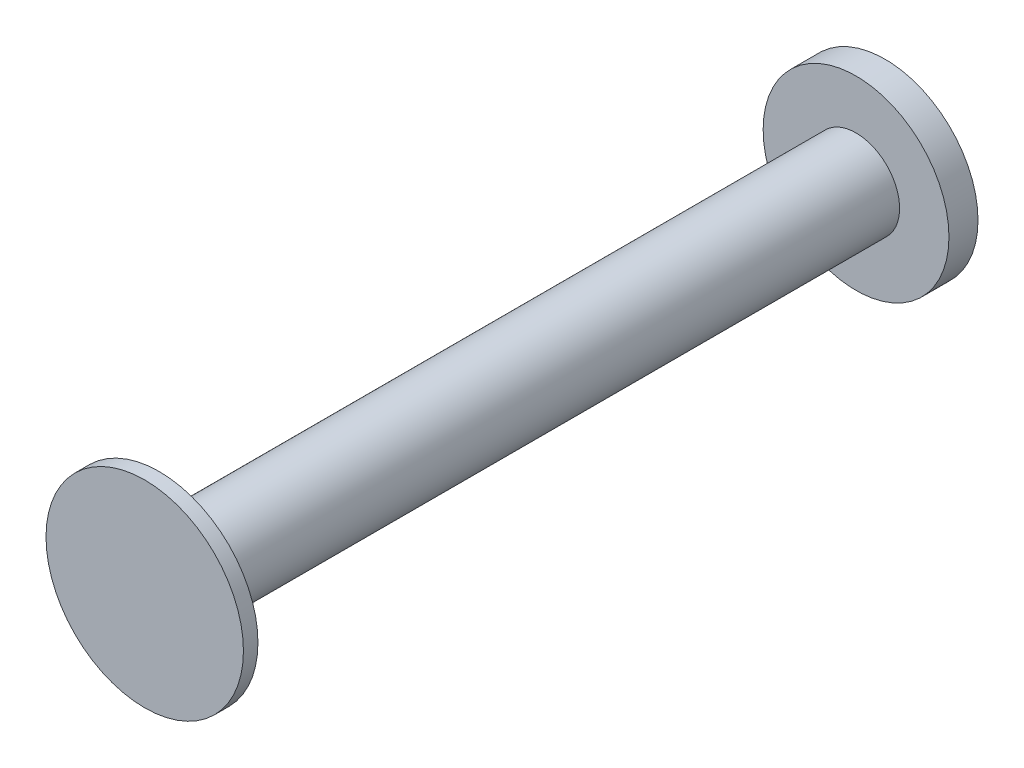
SolidWorks part; units mm, degrees
ref_plane "Front Plane" through (0, 0, 0) normal (0, 0, 1) x (1, 0, 0)
ref_plane "Top Plane" through (0, 0, 0) normal (0, 1, 0) x (1, 0, 0)
ref_plane "Right Plane" through (0, 0, 0) normal (1, 0, 0) x (0, 0, -1)
sketch "Sketch1" plane through (0, 0, 0) normal (0, 0, 1) x (1, 0, 0)
  circle A0 centre (0, 0) radius 20.32
  dimension "D1" = 40.64
extrude "Boss-Extrude1" add sketch "Sketch1" along normal blind 6.35
sketch "Sketch2" plane through (0, 0, 6.35) normal (0, 0, 1) x (1, 0, 0)
  circle A0 centre (0, 0) radius 9.525
  dimension "D1" = 19.05
extrude "Boss-Extrude2" add sketch "Sketch2" along normal blind 152.4
sketch "Sketch3" plane through (0, 0, 158.75) normal (0, 0, 1) x (1, 0, 0)
  circle A0 centre (0, 0) radius 21.59
  dimension "D1" = 43.18
extrude "Boss-Extrude3" add sketch "Sketch3" along normal blind 3.175
